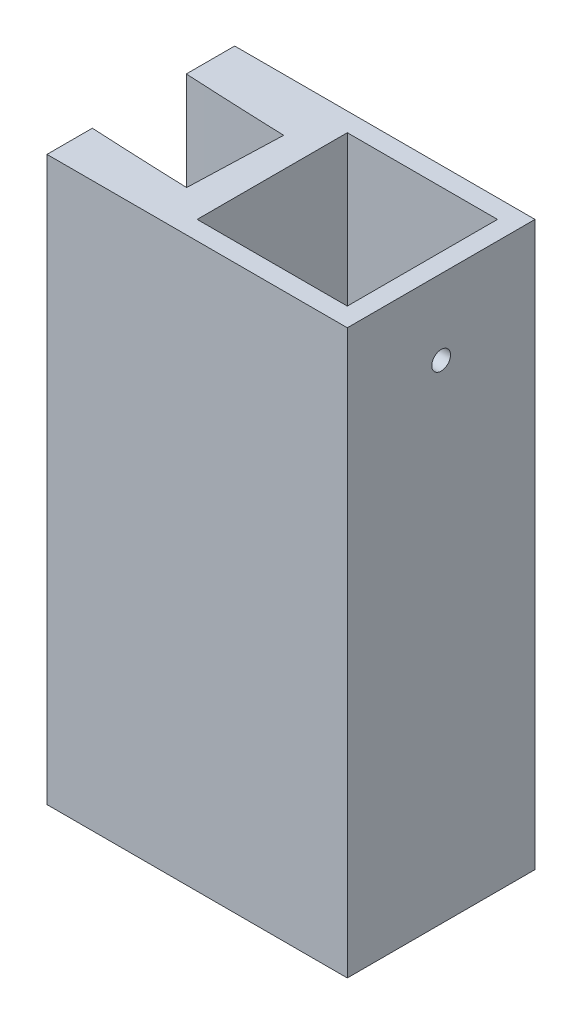
SolidWorks part; units mm, degrees
ref_plane "前视基准面" through (0, 0, 0) normal (0, 0, 1) x (1, 0, 0)
ref_plane "上视基准面" through (0, 0, 0) normal (0, 1, 0) x (1, 0, 0)
ref_plane "右视基准面" through (0, 0, 0) normal (1, 0, 0) x (0, 0, -1)
sketch "草图1" plane through (0, 0, 0) normal (0, 1, 0) x (1, 0, 0)
  line L0 (-25, 12.5) -> (-25, -12.5)
  line L1 (-25, 25) -> (25, 25)
  line L2 (-25, 25) -> (-25, -25)
  line L3 (-25, -25) -> (25, -25)
  line L4 (25, 25) -> (25, -25)
  line L5 (-25, 25) -> (25, -25) construction
  line L6 (-25, -25) -> (25, 25) construction
  line L7 (-25, 25) -> (-55, 25)
  line L8 (-25, 25) -> (-25, -25)
  line L9 (-25, -25) -> (-55, -25)
  line L10 (-55, 25) -> (-55, -25)
  line L11 (25, 12.5) -> (25, 1527.5) construction
  line L12 (25, 1527.5) -> (-26.2196, -11.648)
  arc A0 (25, 12.5) -> (-55, 14.6137) centre (25, 1527.5) cw
  arc A1 (25, -12.5) -> (-55, -10.4207) centre (25, 1527.5) cw
  point P0 (0, 0)
  point P11 (-25, 0)
  dimension "D6" = 1540
  dimension "D1" = 50
  dimension "D2" = 25
  dimension "D3" = 12.5
  dimension "D4" = 30
  dimension "D5" = 1515
extrude "凸台-拉伸1" add sketch "草图1" along normal blind 150
ref_plane "基准面1" through (0, 0, 0) normal (1, 0, 0) x (0, 0, -1)
sketch "草图3" plane through (0, 0, 0) normal (1, 0, 0) x (0, 0, -1)
  line L0 (0, 0) -> (0, 100) construction
  line L1 (0, 100) -> (5, 100)
  line L2 (5, 100) -> (13.6824, 50.7596)
  line L3 (13.6824, 50.7596) -> (13.6824, 0)
  line L4 (25, 0) -> (-25, 0) construction
  line L5 (0, 100) -> (0, 0)
  line L6 (0, 0) -> (13.6824, 0)
  dimension "D1" = 100
  dimension "D2" = 5
  dimension "D3" = 50
  dimension "D4" = 10
revolve "切除-旋转1" cut sketch "草图3" angle 360 about L0
sketch "草图4" plane through (0, 150, 0) normal (0, 1, 0) x (1, 0, 0)
  line L1 (-20, 20) -> (20, 20)
  line L2 (-20, 20) -> (-20, -20)
  line L3 (-20, -20) -> (20, -20)
  line L4 (20, 20) -> (20, -20)
  line L5 (-20, 20) -> (20, -20) construction
  line L6 (-20, -20) -> (20, 20) construction
  point P0 (0, 0)
  dimension "D1" = 40
extrude "切除-拉伸1" cut sketch "草图4" against normal blind 40
sketch "草图5" plane through (25, 0, 0) normal (1, 0, 0) x (0, 0, -1)
  line L1 (-4.25, 135) -> (4.25, 135)
  line L2 (-4.25, 135) -> (-4.25, 125)
  line L3 (-4.25, 125) -> (4.25, 125)
  line L4 (4.25, 135) -> (4.25, 125)
  line L5 (-4.25, 135) -> (4.25, 125) construction
  line L6 (-4.25, 125) -> (4.25, 135) construction
  line L9 (25, 150) -> (-25, 150) construction
  line L10 (0, 130) -> (0, 150) construction
  point P0 (0, 130)
  dimension "D1" = 8.5
  dimension "D2" = 20
  dimension "D3" = 10
hole_wizard "M6 螺纹孔的螺纹孔钻头1" positions "草图6" profile "草图7" hole size "M6" standard "GB"
sketch "草图6" plane through (25, 0, 0) normal (1, 0, 0) x (0, 0, -1)
  point P0 (0, 130)
sketch "草图7" plane through (25, 130, 0) normal (0, 1, 0) x (0, 0, -1)
  line L0 (0, 0) -> (0, 5)
  line L1 (0, 5) -> (2.5, 5)
  line L2 (2.5, 5) -> (2.5, 0)
  line L5 (2.5, 0) -> (0, 0)
  line L11 (0, -6.35) -> (0, 107.95) construction
  dimension "通孔孔直径" = 5
  dimension "通孔孔深度" = 5
sketch "草图8" plane through (0, 150, 0) normal (0, 1, 0) x (1, 0, 0)
  line L0 (-28.7452, -14.0619) -> (-27.8727, 10.9229) construction
  line L1 (-28.7452, -14.0619) -> (-27.8727, 10.9229)
  line L2 (-55, 12.1137) -> (-55, -12.9207)
  line L3 (-55, 25) -> (-55, -25) construction
  arc A0 (-443.1607, 84.1494) -> (-27.8727, 10.9229) centre (25, 1525) ccw construction
  arc A1 (-450.8862, 60.373) -> (-28.7452, -14.0619) centre (25, 1525) ccw construction
  arc A2 (-55, 12.1137) -> (-27.8727, 10.9229) centre (25, 1525) ccw
  arc A3 (-55, -12.9207) -> (-28.7452, -14.0619) centre (25, 1525) ccw
extrude "切除-拉伸2" cut sketch "草图8" against normal up to next
